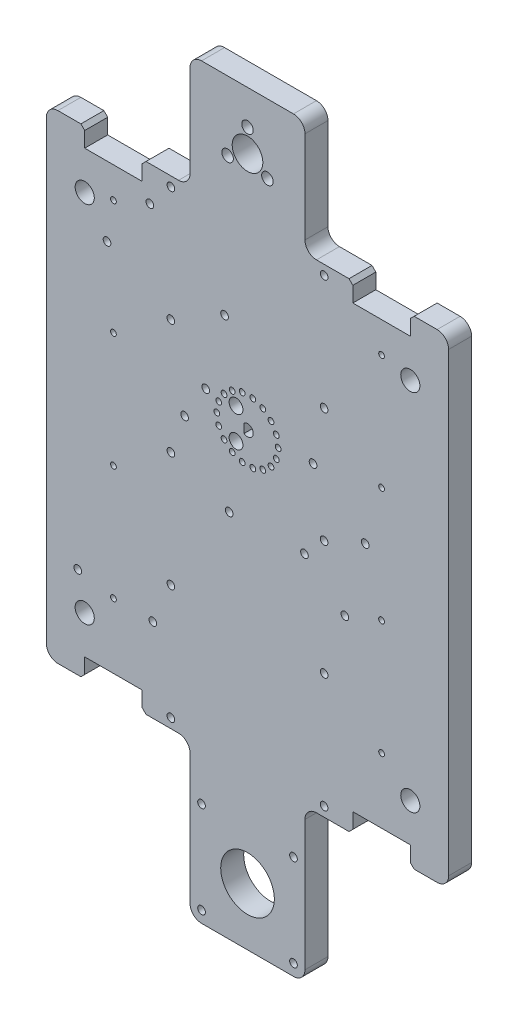
SolidWorks part; units mm, degrees
ref_plane "前视基准面" through (0, 0, 0) normal (0, 0, 1) x (1, 0, 0)
ref_plane "上视基准面" through (0, 0, 0) normal (0, 1, 0) x (1, 0, 0)
ref_plane "右视基准面" through (0, 0, 0) normal (1, 0, 0) x (0, 0, -1)
sketch "草图1" plane through (0, 0, 0) normal (0, 0, 1) x (1, 0, 0)
  line L1 (0, 0) -> (105, 0)
  line L2 (0, 0) -> (0, -125)
  line L3 (0, -125) -> (105, -125)
  line L4 (105, 0) -> (105, -125)
  dimension "D1" = 105
  dimension "D2" = 125
extrude "凸台-拉伸1" add sketch "草图1" along normal blind 6
sketch "草图2" plane through (0, 0, 6) normal (0, 0, 1) x (1, 0, 0)
  line L0 (52.5, 0) -> (52.5, -125) construction
  line L1 (105, 0) -> (0, 0) construction
  line L2 (0, -125) -> (105, -125) construction
  circle A0 centre (32.5, -2.5) radius 1
  circle A1 centre (72.5, -2.5) radius 1
  circle A2 centre (72.5, -32.5) radius 1
  circle A3 centre (72.5, -62.5) radius 1
  circle A4 centre (72.5, -92.5) radius 1
  circle A5 centre (72.5, -122.5) radius 1
  circle A6 centre (32.5, -32.5) radius 1
  circle A7 centre (32.5, -62.5) radius 1
  circle A8 centre (32.5, -92.5) radius 1
  circle A9 centre (32.5, -122.5) radius 1
  circle A11 centre (17.5, -13) radius 0.75
  circle A12 centre (87.5, -13) radius 0.75
  circle A13 centre (87.5, -43) radius 0.75
  circle A14 centre (87.5, -73) radius 0.75
  circle A15 centre (87.5, -103) radius 0.75
  circle A16 centre (17.5, -43) radius 0.75
  circle A17 centre (17.5, -73) radius 0.75
  circle A18 centre (17.5, -103) radius 0.75
  dimension "D1" = 2
  dimension "D2" = 2.5
  dimension "D8" = 1.5
  dimension "D3" = 20
  dimension "D6" = 15
  dimension "D7" = 19.5
  dimension "D4" = 2
  dimension "D5" = 5
  dimension "D9" = 2
  dimension "D10" = 4
extrude "切除-拉伸1" cut sketch "草图2" against normal up to next
fillet "圆角1" radius 3 4 edges at (105, -125, 3) (0, -125, 3) (0, 0, 3) (105, 0, 3)
sketch "草图3" plane through (0, 0, 6) normal (0, 0, 1) x (1, 0, 0)
  line L0 (52.5, 0) -> (52.5, -125) construction
  line L1 (102, 0) -> (3, 0) construction
  line L2 (3, -125) -> (102, -125) construction
  line L3 (32.5, -32.5) -> (32.5, -62.5) construction
  line L4 (32.5, -47.5) -> (52.5, -47.5) construction
  line L13 (51.6, -46.3) -> (51.6, -48.7)
  circle A3 centre (52.5, -47.5) radius 8 construction
  arc A24 (51.6, -48.7) -> (51.6, -46.3) centre (52.5, -47.5) ccw
  circle A25 centre (44.5, -47.5) radius 0.75
  circle A26 centre (44.9825, -44.7638) radius 0.75
  circle A44 centre (49.5, -43.5) radius 1.8
  circle A45 centre (49.5, -51.5) radius 1.8
  circle A48 centre (46.3716, -42.3577) radius 0.75
  circle A49 centre (48.5, -40.5718) radius 0.75
  circle A50 centre (51.1108, -39.6215) radius 0.75
  circle A51 centre (53.8892, -39.6215) radius 0.75
  circle A52 centre (56.5, -40.5718) radius 0.75
  circle A53 centre (58.6284, -42.3577) radius 0.75
  circle A54 centre (60.0175, -44.7638) radius 0.75
  circle A55 centre (60.5, -47.5) radius 0.75
  circle A56 centre (60.0175, -50.2362) radius 0.75
  circle A57 centre (58.6284, -52.6423) radius 0.75
  circle A58 centre (56.5, -54.4282) radius 0.75
  circle A59 centre (53.8892, -55.3785) radius 0.75
  circle A60 centre (51.1108, -55.3785) radius 0.75
  circle A61 centre (48.5, -54.4282) radius 0.75
  circle A62 centre (46.3716, -52.6423) radius 0.75
  circle A63 centre (44.9825, -50.2362) radius 0.75
  point P52 (52.5, -47.5)
  point P53 (52.5, -47.5)
  point P54 (52.5, -47.5)
extrude "切除-拉伸2" cut sketch "草图3" against normal up to next
sketch "Sketch2" plane through (0, 0, 0) normal (0, 0, -1) x (-1, 0, 0)
  line L0 (-17.5, -13) -> (-51.1108, -39.6215) construction
  line L1 (-17.5, -103) -> (-46.3716, -52.6423) construction
  line L2 (-52.7793, -29.462) -> (-46.5081, -24.4949) construction
  line L3 (-12.1791, -94.1859) -> (-27.7947, -103.1388) construction
  line L4 (-87.5, -73) -> (-60.0175, -50.2362) construction
  line L5 (-52.7793, -29.462) -> (-41.6033, -43.5722) construction
  line L6 (-36.0769, -52.5035) -> (-51.6925, -61.4564) construction
  line L7 (-12.1791, -94.1859) -> (-8.2001, -101.1261) construction
  line L8 (-51.6925, -61.4564) -> (-47.7134, -68.3967) construction
  line L9 (-27.0075, -9.0494) -> (-15.8315, -23.1595) construction
  line L10 (-69.6092, -46.4945) -> (-58.1271, -60.3567) construction
  line L11 (-89.3904, -62.8794) -> (-77.9083, -76.7416) construction
  line L12 (-58.1271, -60.3567) -> (-67.3686, -68.0115) construction
  line L13 (-89.3904, -62.8794) -> (-83.2295, -57.7763) construction
  circle A6 centre (-27.0075, -9.0494) radius 1
  circle A7 centre (-15.8315, -23.1595) radius 1
  circle A9 centre (-41.6033, -43.5722) radius 1
  circle A11 centre (-27.7947, -103.1388) radius 1
  circle A13 centre (-36.0769, -52.5035) radius 1
  circle A15 centre (-77.9083, -76.7416) radius 1
  circle A16 centre (-69.6092, -46.4945) radius 1
  circle A28 centre (-46.5081, -24.4949) radius 1
  circle A29 centre (-8.2001, -101.1261) radius 1
  circle A30 centre (-47.7134, -68.3967) radius 1
  circle A31 centre (-67.3686, -68.0115) radius 1
  circle A32 centre (-83.2295, -57.7763) radius 1
  point P24 (-19.9869, -98.6623)
  point P26 (-21.4195, -16.1044)
  point P29 (-83.6494, -69.8105)
  point P33 (-63.8682, -53.4256)
  point P37 (-47.1913, -36.5171)
  point P42 (-43.8847, -56.98)
extrude "Cut-Extrude1" cut sketch "Sketch2" against normal up to next
sketch "Sketch3" plane through (0, 0, 0) normal (0, 0, -1) x (-1, 0, 0)
  line L0 (-52.5, 0) -> (-52.5, -125) construction
  line L1 (-52.5, -125) -> (-37.5, -125)
  line L2 (-102, 0) -> (-3, 0) construction
  line L3 (-3, -125) -> (-102, -125) construction
  line L4 (-52.5, 0) -> (-37.5, 0)
  line L5 (-52.5, 0) -> (-67.5, 0)
  line L6 (-67.5, 0) -> (-67.5, 30)
  line L7 (-67.5, 30) -> (-37.5, 30)
  line L8 (-37.5, 30) -> (-37.5, 0)
  line L9 (-37.5, -125) -> (-37.5, -165)
  line L10 (-37.5, -165) -> (-67.5, -165)
  line L11 (-67.5, -165) -> (-67.5, -125)
  line L12 (-67.5, -125) -> (-52.5, -125)
extrude "Boss-Extrude1" add sketch "Sketch3" against normal blind 6
sketch "Sketch5" plane through (0, 0, 0) normal (0, 0, -1) x (-1, 0, 0)
  line L0 (-52.5, 15) -> (-52.5, 21) construction
  line L1 (-67.5, 30) -> (-67.5, 0) construction
  circle A0 centre (-52.5, 15) radius 10 construction
  circle A1 centre (-52.5, 15) radius 4
  circle A2 centre (-52.5, 21) radius 1.5
  circle A8 centre (-47.3038, 12) radius 1.5
  circle A9 centre (-57.6962, 12) radius 1.5
  point P13 (-52.5, 15)
  point P14 (0, 0)
  dimension "D1" = 6
  dimension "D2" = 15
extrude "Cut-Extrude2" cut sketch "Sketch5" against normal up to next
fillet "Fillet1" radius 3 4 edges at (37.5, 0, 3) (37.5, 30, 3) (67.5, 30, 3) (67.5, 0, 3)
sketch "Sketch6" plane through (0, 0, 0) normal (0, 0, -1) x (-1, 0, 0)
  line L0 (-3, -125) -> (-37.5, -125) construction
  line L1 (-102, 0) -> (-70.5, 0) construction
  line L2 (-105, -122) -> (-105, -3) construction
  line L3 (0, -3) -> (0, -122) construction
  circle A0 centre (-95, -15) radius 2.5
  circle A1 centre (-95, -15) radius 4.5 construction
  circle A2 centre (-95, -110) radius 2.5
  circle A3 centre (-10, -15) radius 2.5
  circle A4 centre (-10, -110) radius 2.5
  dimension "D1" = 15
  dimension "D3" = 15
  dimension "D5" = 10
  dimension "D2" = 10
  dimension "D4" = 10
extrude "Cut-Extrude3" cut sketch "Sketch6" against normal up to next
sketch "Sketch8" plane through (0, 0, 0) normal (0, 0, -1) x (-1, 0, 0)
  line L0 (-67.5, -165) -> (-37.5, -165) construction
  line L1 (-67.5, -125) -> (-67.5, -165) construction
  line L2 (-37.5, -165) -> (-37.5, -125) construction
  line L3 (-67.5, -125) -> (-102, -125) construction
  circle A0 centre (-64.5, -162) radius 1
  circle A1 centre (-40.5, -162) radius 1
  circle A2 centre (-64.5, -138) radius 1
  circle A3 centre (-40.5, -138) radius 1
  circle A4 centre (-52.5, -150) radius 7
  dimension "D1" = 3
  dimension "D3" = 3
  dimension "D4" = 13
  dimension "D5" = 15
  dimension "D2" = 3
  dimension "D6" = 15
extrude "Cut-Extrude4" cut sketch "Sketch8" against normal up to next
fillet "Fillet2" radius 3 4 edges at (37.5, -125, 3) (37.5, -165, 3) (67.5, -125, 3) (67.5, -165, 3)
sketch "Sketch9" plane through (0, -125, 0) normal (0, -1, 0) x (1, 0, 0)
  line L0 (52.5, 6) -> (52.5, 0) construction
  line L1 (64.5, 6) -> (40.5, 6) construction
  line L2 (64.5, 0) -> (40.5, 0) construction
  line L3 (52.5, 3) -> (17.5, 3) construction
  line L4 (3, 6) -> (34.5, 6) construction
  line L5 (10, 0) -> (25, 0)
  line L6 (10, 0) -> (10, 6)
  line L7 (10, 6) -> (25, 6)
  line L8 (25, 0) -> (25, 6)
  line L9 (10, 0) -> (25, 6) construction
  line L10 (10, 6) -> (25, 0) construction
  line L11 (80, 0) -> (80, 6)
  line L12 (95, 0) -> (80, 0)
  line L13 (95, 0) -> (95, 6)
  line L14 (95, 6) -> (80, 6)
  dimension "D1" = 15
  dimension "D2" = 35
extrude "Cut-Extrude5" cut sketch "Sketch9" against normal blind 5
sketch "Sketch10" plane through (0, 0, 0) normal (0, 1, 0) x (1, 0, 0)
  line L4 (25, 0) -> (10, 0)
  line L5 (25, -6) -> (25, 0)
  line L6 (10, -6) -> (25, -6)
  line L7 (10, 0) -> (10, -6)
  line L8 (25, 0) -> (10, 0)
  line L9 (25, -6) -> (25, 0)
  line L10 (10, -6) -> (25, -6)
  line L11 (10, 0) -> (10, -6)
  line L12 (95, -6) -> (95, 0)
  line L13 (80, -6) -> (95, -6)
  line L14 (80, 0) -> (80, -6)
  line L15 (95, 0) -> (80, 0)
  line L16 (95, -6) -> (95, 0)
  line L17 (80, -6) -> (95, -6)
  line L18 (80, 0) -> (80, -6)
  line L19 (95, 0) -> (80, 0)
  dimension "D1" = 0
  dimension "D2" = 0
extrude "Cut-Extrude6" cut sketch "Sketch10" against normal blind 5
chamfer "Chamfer1" distance 1 angle 45 8 edges at (10, -125, 3) (25, -125, 3) (80, -125, 3) (95, -125, 3) (95, 0, 3) (80, 0, 3) (25, 0, 3) (10, 0, 3)
